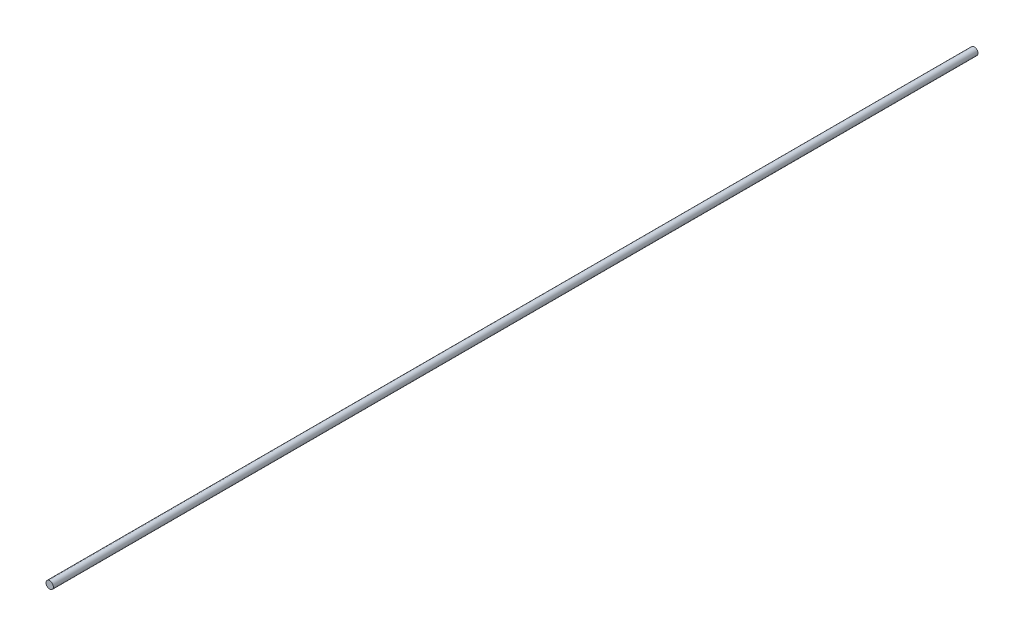
SolidWorks part; units mm, degrees
material "Chrome Stainless Steel"
ref_plane "Front Plane" through (0, 0, 0) normal (0, 0, 1) x (1, 0, 0)
ref_plane "Top Plane" through (0, 0, 0) normal (0, 1, 0) x (1, 0, 0)
ref_plane "Right Plane" through (0, 0, 0) normal (1, 0, 0) x (0, 0, -1)
sketch "Sketch1" plane through (0, 0, 0) normal (0, 0, 1) x (1, 0, 0)
  circle A0 centre (0, 0) radius 4
  dimension "D1" = 8
extrude "Boss-Extrude1" add sketch "Sketch1" along normal blind 1000
